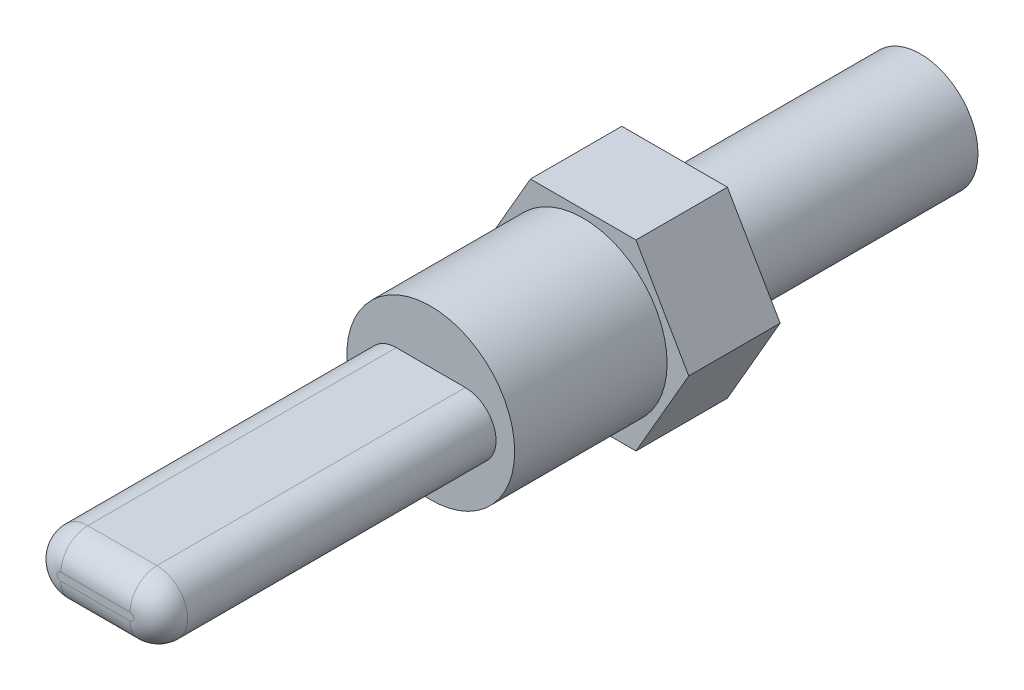
SolidWorks part; units mm, degrees
ref_plane "Front Plane" through (0, 0, 0) normal (0, 0, 1) x (1, 0, 0)
ref_plane "Top Plane" through (0, 0, 0) normal (0, 1, 0) x (1, 0, 0)
ref_plane "Right Plane" through (0, 0, 0) normal (1, 0, 0) x (0, 0, -1)
sketch "Sketch1" plane through (0, 0, 0) normal (0, 0, 1) x (1, 0, 0)
  circle A0 centre (0, 0) radius 1.5
  dimension "D1" = 3
extrude "Boss-Extrude1" add sketch "Sketch1" along normal blind 6.4
sketch "Sketch2" plane through (0, 0, 6.4) normal (0, 0, 1) x (1, 0, 0)
  line L0 (1.65, 0) -> (-1.65, 0) construction
  line L1 (1.3741, -2.38) -> (2.7482, 0)
  line L2 (2.7482, 0) -> (1.3741, 2.38)
  line L3 (1.3741, 2.38) -> (-1.3741, 2.38)
  line L4 (-1.3741, 2.38) -> (-2.7482, 0)
  line L5 (-2.7482, 0) -> (-1.3741, -2.38)
  line L6 (-1.3741, -2.38) -> (1.3741, -2.38)
  circle A0 centre (0, 0) radius 2.38 construction
  dimension "D1" = 4.76
  dimension "D2" = 0
extrude "Boss-Extrude2" add sketch "Sketch2" along normal blind 2.38
sketch "Sketch3" plane through (0, 0, 8.78) normal (0, 0, 1) x (1, 0, 0)
  circle A0 centre (0, 0) radius 2.185
  dimension "D1" = 4.37
extrude "Boss-Extrude3" add sketch "Sketch3" along normal blind 3.97
sketch "Sketch4" plane through (0, 0, 12.75) normal (0, 0, 1) x (1, 0, 0)
  line L0 (-0.9, 0) -> (0.9, 0) construction
  line L1 (3.023, 0) -> (-3.023, 0) construction
  line L2 (-0.9, 0.8) -> (0.9, 0.8)
  line L3 (-0.9, -0.8) -> (0.9, -0.8)
  line L4 (0, -2.618) -> (0, 2.618) construction
  arc A0 (-0.9, 0.8) -> (-0.9, -0.8) centre (-0.9, 0) ccw
  arc A1 (0.9, -0.8) -> (0.9, 0.8) centre (0.9, 0) ccw
  point P5 (0, 0)
  dimension "D3" = 0.8
  dimension "D1" = 0.9
  dimension "D2" = 0.9
extrude "Boss-Extrude4" add sketch "Sketch4" along normal blind 8.73
fillet "Fillet1" radius 0.7 4 edges at (0, 0.8, 21.48) (1.7, 0, 21.48) (0, -0.8, 21.48) (-1.7, 0, 21.48)
